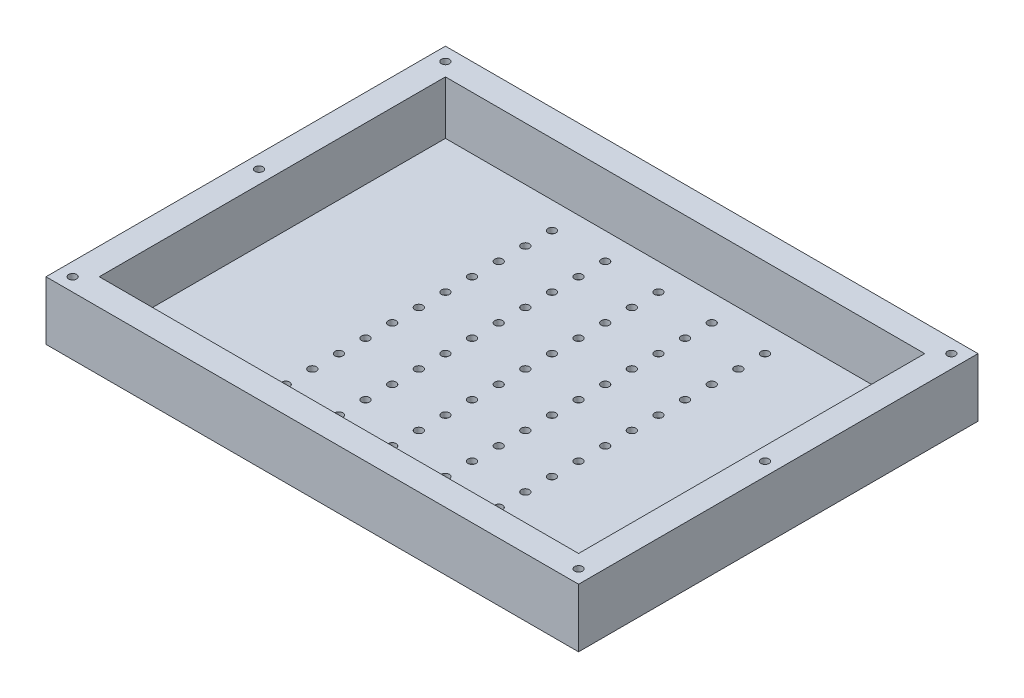
SolidWorks part; units mm, degrees
ref_plane "Front Plane" through (0, 0, 0) normal (0, 0, 1) x (1, 0, 0)
ref_plane "Top Plane" through (0, 0, 0) normal (0, 1, 0) x (1, 0, 0)
ref_plane "Right Plane" through (0, 0, 0) normal (1, 0, 0) x (0, 0, -1)
sketch "Sketch1" plane through (0, 0, 0) normal (0, 1, 0) x (1, 0, 0)
  line L1 (-100, 75) -> (100, 75)
  line L2 (-100, 75) -> (-100, -75)
  line L3 (-100, -75) -> (100, -75)
  line L4 (100, 75) -> (100, -75)
  line L5 (-100, 75) -> (100, -75) construction
  line L6 (-100, -75) -> (100, 75) construction
  point P0 (0, 0)
  dimension "D1" = 200
  dimension "D2" = 150
extrude "Boss-Extrude1" add sketch "Sketch1" along normal blind 2
sketch "Sketch2" plane through (0, 2, 0) normal (0, 1, 0) x (1, 0, 0)
  line L0 (0, 75) -> (0, -75) construction
  line L1 (100, 75) -> (-100, 75) construction
  line L2 (-100, -75) -> (100, -75) construction
  line L3 (10, 75) -> (10, -75) construction
  line L4 (-10, 75) -> (-10, -75) construction
  line L6 (-30, 0) -> (10, 0) construction
  line L7 (30, 75) -> (30, -75) construction
  circle A0 centre (0, -5) radius 1.5
  circle A1 centre (0, -15) radius 1.5
  circle A2 centre (0, -25) radius 1.5
  circle A3 centre (0, -35) radius 1.5
  circle A4 centre (0, -45) radius 1.5
  circle A5 centre (0, -55) radius 1.5
  circle A6 centre (0, 55) radius 1.5
  circle A7 centre (0, 45) radius 1.5
  circle A8 centre (0, 35) radius 1.5
  circle A9 centre (0, 25) radius 1.5
  circle A10 centre (0, 15) radius 1.5
  circle A11 centre (0, 5) radius 1.5
  circle A12 centre (20, -55) radius 1.5
  circle A13 centre (20, -45) radius 1.5
  circle A14 centre (20, -35) radius 1.5
  circle A15 centre (20, -25) radius 1.5
  circle A16 centre (20, -15) radius 1.5
  circle A17 centre (20, -5) radius 1.5
  circle A18 centre (20, 5) radius 1.5
  circle A19 centre (20, 15) radius 1.5
  circle A20 centre (20, 25) radius 1.5
  circle A21 centre (20, 35) radius 1.5
  circle A22 centre (20, 45) radius 1.5
  circle A23 centre (20, 55) radius 1.5
  circle A24 centre (-20, -55) radius 1.5
  circle A25 centre (-20, -45) radius 1.5
  circle A26 centre (-20, -35) radius 1.5
  circle A27 centre (-20, -25) radius 1.5
  circle A28 centre (-20, -15) radius 1.5
  circle A29 centre (-20, -5) radius 1.5
  circle A30 centre (-20, 5) radius 1.5
  circle A31 centre (-20, 15) radius 1.5
  circle A32 centre (-20, 25) radius 1.5
  circle A33 centre (-20, 35) radius 1.5
  circle A34 centre (-20, 45) radius 1.5
  circle A35 centre (-20, 55) radius 1.5
  circle A36 centre (40, -35) radius 1.5
  circle A37 centre (40, -45) radius 1.5
  circle A38 centre (40, -55) radius 1.5
  circle A39 centre (40, -5) radius 1.5
  circle A40 centre (40, -15) radius 1.5
  circle A41 centre (40, -25) radius 1.5
  circle A42 centre (40, 25) radius 1.5
  circle A43 centre (40, 15) radius 1.5
  circle A44 centre (40, 5) radius 1.5
  circle A45 centre (40, 55) radius 1.5
  circle A46 centre (40, 45) radius 1.5
  circle A47 centre (40, 35) radius 1.5
  circle A48 centre (-40, -55) radius 1.5
  circle A49 centre (-40, -45) radius 1.5
  circle A50 centre (-40, -35) radius 1.5
  circle A51 centre (-40, -25) radius 1.5
  circle A52 centre (-40, -15) radius 1.5
  circle A53 centre (-40, -5) radius 1.5
  circle A54 centre (-40, 15) radius 1.5
  circle A55 centre (-40, 5) radius 1.5
  circle A56 centre (-40, 35) radius 1.5
  circle A57 centre (-40, 25) radius 1.5
  circle A58 centre (-40, 55) radius 1.5
  circle A59 centre (-40, 45) radius 1.5
  point P73 (-10, 0)
  dimension "D3" = 3
  dimension "D4" = 3
  dimension "D5" = 3
  dimension "D9" = 3
  dimension "D10" = 3
  dimension "D11" = 3
  dimension "D1" = 10
  dimension "D2" = 10
  dimension "D6" = 5
  dimension "D7" = 10
  dimension "D8" = 10
  dimension "D12" = 10
  dimension "D13" = 10
  dimension "D14" = 10
extrude "Cut-Extrude1" cut sketch "Sketch2" against normal through all
sketch "Sketch3" plane through (0, 2, 0) normal (0, 1, 0) x (1, 0, 0)
  line L8 (90, -65) -> (90, 65)
  line L9 (90, 65) -> (-90, 65)
  line L10 (-90, 65) -> (-90, -65)
  line L11 (-90, -65) -> (90, -65)
  line L12 (90, -65) -> (90, 65)
  line L13 (90, 65) -> (-90, 65)
  line L14 (-90, 65) -> (-90, -65)
  line L15 (-90, -65) -> (90, -65)
  line L20 (100, -75) -> (100, 75)
  line L21 (100, 75) -> (-100, 75)
  line L22 (-100, 75) -> (-100, -75)
  line L23 (-100, -75) -> (100, -75)
  line L24 (100, -75) -> (100, 75)
  line L25 (100, 75) -> (-100, 75)
  line L26 (-100, 75) -> (-100, -75)
  line L27 (-100, -75) -> (100, -75)
  dimension "D1" = 10
  dimension "D2" = 0
extrude "Boss-Extrude2" add sketch "Sketch3" along normal blind 20
sketch "Sketch4" plane through (0, 0, 0) normal (0, -1, 0) x (1, 0, 0)
  line L0 (100, 75) -> (100, -75) construction
  line L1 (-100, 75) -> (100, 75) construction
  line L3 (100, -75) -> (-100, -75) construction
  line L4 (-100, -75) -> (-100, 75) construction
  circle A0 centre (95, 70) radius 1.5
  circle A1 centre (95, -70) radius 1.5
  circle A2 centre (-95, 70) radius 1.5
  circle A3 centre (-95, -70) radius 1.5
  circle A4 centre (95, 0) radius 1.5
  circle A5 centre (-95, 0) radius 1.5
  point P16 (0, 0)
  point P18 (87.6858, -75)
  dimension "D1" = 3
  dimension "D6" = 3
  dimension "D9" = 3
  dimension "D10" = 3
  dimension "D13" = 3
  dimension "D17" = 3
  dimension "D2" = 5
  dimension "D3" = 5
  dimension "D4" = 5
  dimension "D5" = 5
  dimension "D7" = 5
  dimension "D8" = 5
  dimension "D11" = 5
  dimension "5" = 5
  dimension "D12" = 5
  dimension "D14" = 75
  dimension "D15" = 75
  dimension "D16" = 5
extrude "Cut-Extrude2" cut sketch "Sketch4" against normal through all
sketch "Sketch5" plane through (0, 0, 0) normal (0, -1, 0) x (1, 0, 0)
  circle A0 centre (95, 70) radius 3
  circle A1 centre (95, -70) radius 3
  circle A2 centre (-95, 70) radius 3
  circle A3 centre (-95, -70) radius 3
  dimension "D1" = 6
  dimension "D2" = 6
  dimension "D3" = 6
  dimension "D4" = 6
extrude "Cut-Extrude3" cut sketch "Sketch5" against normal blind 17
